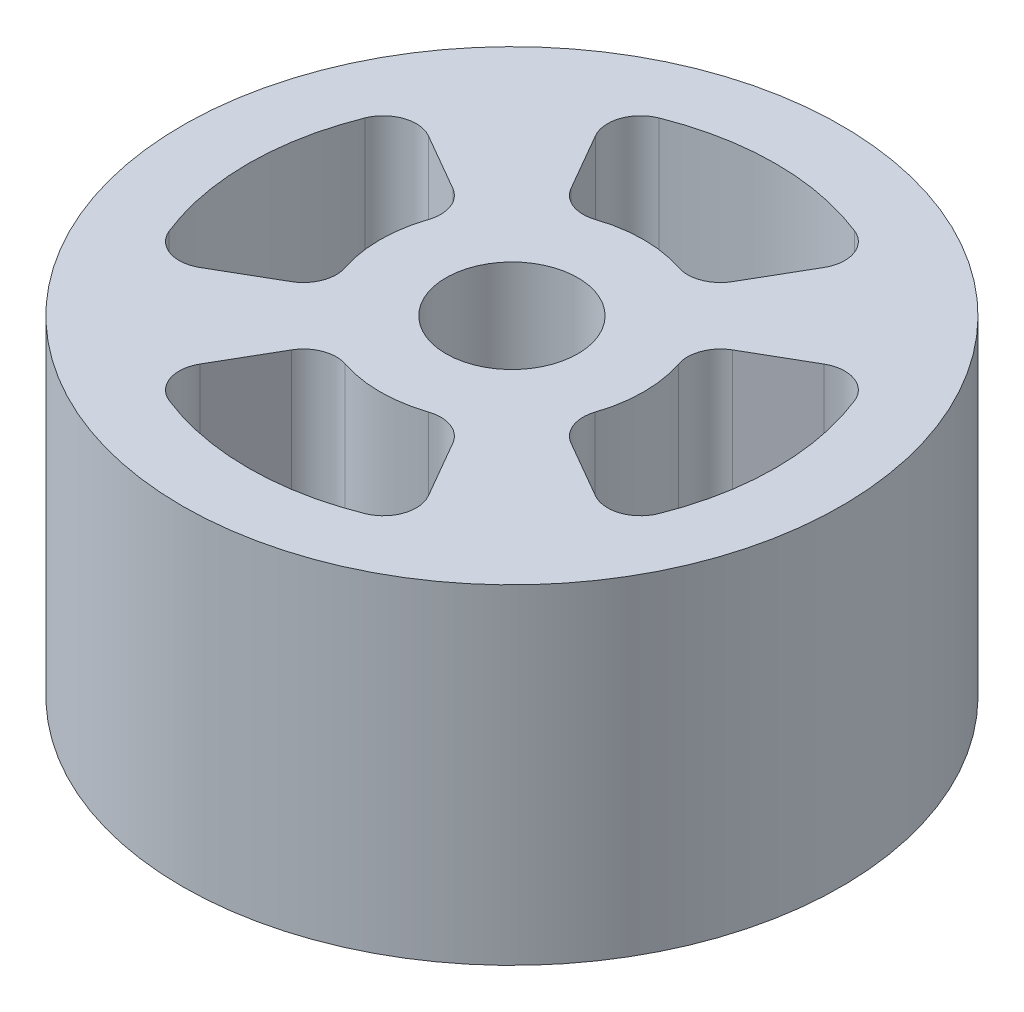
SolidWorks part; units mm, degrees
material "ABS"
ref_plane "前视基准面" through (0, 0, 0) normal (0, 0, 1) x (1, 0, 0)
ref_plane "上视基准面" through (0, 0, 0) normal (0, 1, 0) x (1, 0, 0)
ref_plane "右视基准面" through (0, 0, 0) normal (1, 0, 0) x (0, 0, -1)
sketch "草图1" plane through (0, 0, 0) normal (0, 1, 0) x (1, 0, 0)
  line L0 (-4, -6.9282) -> (-8, -13.8564)
  line L9 (-4, 6.9282) -> (-8, 13.8564)
  line L10 (-6.9282, 4) -> (-13.8564, 8)
  line L11 (-6.9282, -4) -> (-13.8564, -8)
  line L12 (4, -6.9282) -> (8, -13.8564)
  line L13 (6.9282, -4) -> (13.8564, -8)
  line L14 (6.9282, 4) -> (13.8564, 8)
  line L15 (4, 6.9282) -> (8, 13.8564)
  line L16 (0, 8) -> (0, 16) construction
  circle A0 centre (0, 0) radius 20
  circle A1 centre (0, 0) radius 4
  arc A3 (-13.8564, 8) -> (-13.8564, -8) centre (0, 0) ccw
  arc A4 (-6.9282, 4) -> (-6.9282, -4) centre (0, 0) ccw
  arc A5 (4, 6.9282) -> (-4, 6.9282) centre (0, 0) ccw
  arc A6 (8, 13.8564) -> (-8, 13.8564) centre (0, 0) ccw
  arc A7 (-4, -6.9282) -> (4, -6.9282) centre (0, 0) ccw
  arc A8 (-8, -13.8564) -> (8, -13.8564) centre (0, 0) ccw
  arc A9 (13.8564, -8) -> (13.8564, 8) centre (0, 0) ccw
  arc A10 (6.9282, -4) -> (6.9282, 4) centre (0, 0) ccw
  point P18 (0, 0)
  dimension "D1" = 40
  dimension "D2" = 8
  dimension "D3" = 32
  dimension "D4" = 16
extrude "凸台-拉伸1" add sketch "草图1" along normal blind 20
fillet "圆角1" radius 2 16 edges at (-13.8564, 10, -8) (-13.8564, 10, 8) (-6.9282, 10, 4) (-6.9282, 10, -4) (4, 10, 6.9282) (8, 10, 13.8564) (-8, 10, 13.8564) (-4, 10, 6.9282) (13.8564, 10, 8) (6.9282, 10, 4) (6.9282, 10, -4) (13.8564, 10, -8) (4, 10, -6.9282) (-4, 10, -6.9282) (-8, 10, -13.8564) (8, 10, -13.8564)
